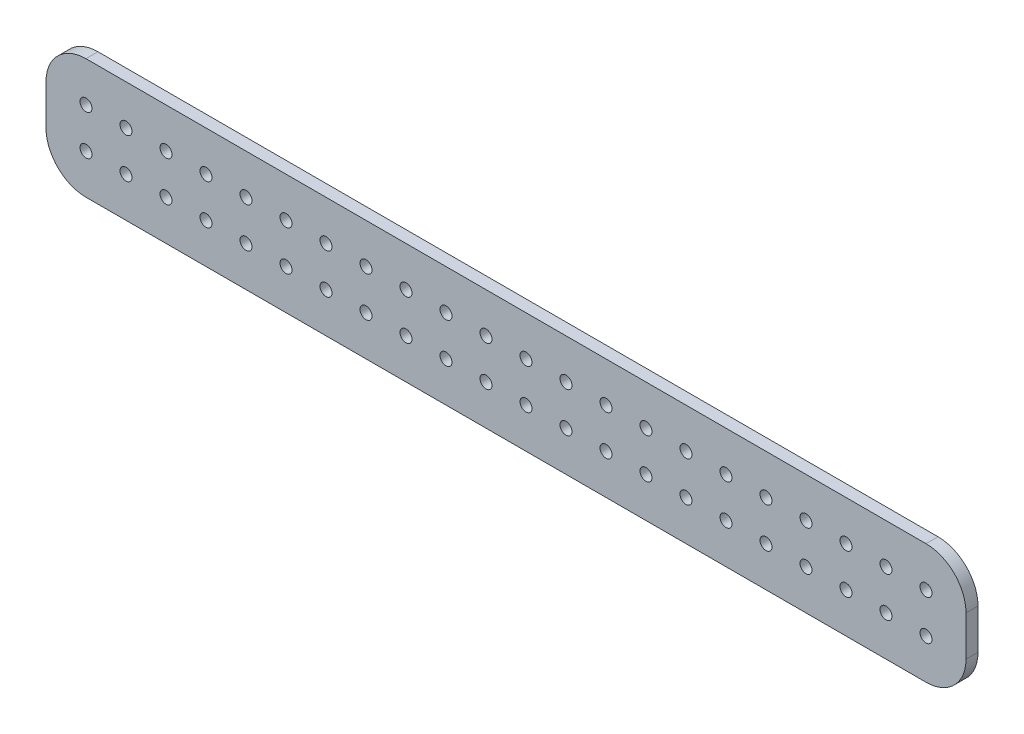
SolidWorks part; units mm, degrees
material "Maple"
ref_plane "Front Plane" through (0, 0, 0) normal (0, 0, 1) x (1, 0, 0)
ref_plane "Top Plane" through (0, 0, 0) normal (0, 1, 0) x (1, 0, 0)
ref_plane "Right Plane" through (0, 0, 0) normal (1, 0, 0) x (0, 0, -1)
sketch "Sketch1" plane through (0, 0, 0) normal (0, 0, 1) x (1, 0, 0)
  line L0 (-115, 5) -> (-105, 5) construction
  line L1 (-105, 15) -> (105, 15)
  line L2 (-115, 5) -> (-115, -5)
  line L3 (-105, -15) -> (105, -15)
  line L4 (115, 5) -> (115, -5)
  line L5 (-115, 15) -> (115, -15) construction
  line L6 (-115, -15) -> (115, 15) construction
  line L7 (-105, 5) -> (-95, 5) construction
  line L8 (-95, 5) -> (-85, 5) construction
  line L9 (-85, 5) -> (-75, 5) construction
  line L10 (-75, 5) -> (-65, 5) construction
  line L11 (-65, 5) -> (-55, 5) construction
  line L12 (-55, 5) -> (-45, 5) construction
  line L13 (-45, 5) -> (-35, 5) construction
  line L14 (-35, 5) -> (-25, 5) construction
  line L15 (-25, 5) -> (-15, 5) construction
  line L16 (-15, 5) -> (-5, 5) construction
  line L17 (-5, 5) -> (5, 5) construction
  line L18 (5, 5) -> (15, 5) construction
  line L19 (15, 5) -> (25, 5) construction
  line L20 (25, 5) -> (35, 5) construction
  line L21 (35, 5) -> (45, 5) construction
  line L22 (45, 5) -> (55, 5) construction
  line L23 (55, 5) -> (65, 5) construction
  line L24 (65, 5) -> (75, 5) construction
  line L25 (75, 5) -> (85, 5) construction
  line L26 (85, 5) -> (95, 5) construction
  line L27 (95, 5) -> (105, 5) construction
  line L28 (-115, -5) -> (-85, -5) construction
  line L29 (-85, -5) -> (-75, -5) construction
  line L30 (-75, -5) -> (-65, -5) construction
  line L31 (-65, -5) -> (-55, -5) construction
  line L32 (-55, -5) -> (-45, -5) construction
  line L33 (-45, -5) -> (-35, -5) construction
  line L34 (-35, -5) -> (-25, -5) construction
  line L35 (-25, -5) -> (-15, -5) construction
  line L36 (-15, -5) -> (-5, -5) construction
  line L37 (-5, -5) -> (5, -5) construction
  line L38 (5, -5) -> (15, -5) construction
  line L39 (15, -5) -> (25, -5) construction
  line L40 (25, -5) -> (35, -5) construction
  line L41 (35, -5) -> (45, -5) construction
  line L42 (45, -5) -> (55, -5) construction
  line L43 (55, -5) -> (65, -5) construction
  line L44 (65, -5) -> (75, -5) construction
  line L45 (75, -5) -> (85, -5) construction
  line L46 (85, -5) -> (95, -5) construction
  line L47 (95, -5) -> (105, -5) construction
  line L48 (105, 5) -> (105, -5) construction
  line L50 (-105, -5) -> (-105, -15) construction
  line L249 (115, -5) -> (115, -15) construction
  line L270 (-105, -5) -> (-105, 5) construction
  line L271 (-95, 5) -> (-95, -5) construction
  arc A0 (115, -5) -> (105, -15) centre (105, -5) cw
  arc A1 (115, 5) -> (105, 15) centre (105, 5) ccw
  arc A2 (-105, -15) -> (-115, -5) centre (-105, -5) cw
  arc A3 (-105, 15) -> (-115, 5) centre (-105, 5) ccw
  circle A4 centre (-105, 5) radius 1.5
  circle A5 centre (-95, 5) radius 1.5
  circle A6 centre (-85, 5) radius 1.5
  circle A7 centre (-75, 5) radius 1.5
  circle A8 centre (-65, 5) radius 1.5
  circle A9 centre (-55, 5) radius 1.5
  circle A10 centre (-45, 5) radius 1.5
  circle A11 centre (-35, 5) radius 1.5
  circle A12 centre (-25, 5) radius 1.5
  circle A13 centre (-15, 5) radius 1.5
  circle A14 centre (-5, 5) radius 1.5
  circle A16 centre (15, 5) radius 1.5
  circle A18 centre (25, 5) radius 1.5
  circle A19 centre (5, 5) radius 1.5
  circle A20 centre (35, 5) radius 1.5
  circle A21 centre (45, 5) radius 1.5
  circle A22 centre (55, 5) radius 1.5
  circle A23 centre (65, 5) radius 1.5
  circle A24 centre (75, 5) radius 1.5
  circle A25 centre (85, 5) radius 1.5
  circle A26 centre (95, 5) radius 1.5
  circle A29 centre (-85, -5) radius 1.5
  circle A30 centre (-75, -5) radius 1.5
  circle A31 centre (-65, -5) radius 1.5
  circle A32 centre (-55, -5) radius 1.5
  circle A33 centre (-45, -5) radius 1.5
  circle A34 centre (-35, -5) radius 1.5
  circle A35 centre (-25, -5) radius 1.5
  circle A36 centre (-15, -5) radius 1.5
  circle A37 centre (-5, -5) radius 1.5
  circle A38 centre (5, -5) radius 1.5
  circle A39 centre (15, -5) radius 1.5
  circle A40 centre (35, -5) radius 1.5
  circle A41 centre (45, -5) radius 1.5
  circle A42 centre (25, -5) radius 1.5
  circle A43 centre (55, -5) radius 1.5
  circle A44 centre (65, -5) radius 1.5
  circle A45 centre (75, -5) radius 1.5
  circle A46 centre (85, -5) radius 1.5
  circle A47 centre (95, -5) radius 1.5
  circle A48 centre (105, -5) radius 1.5
  circle A239 centre (105, 5) radius 1.5
  circle A263 centre (-105, -5) radius 1.5
  circle A264 centre (-95, -5) radius 1.5
  point P0 (0, 0)
  point P104 (115, 0)
  dimension "D3" = 230
  dimension "D5" = 10
  dimension "D1" = 3
  dimension "D2" = 30
  dimension "D6" = 10
extrude "Boss-Extrude1" add sketch "Sketch1" along normal blind 3
